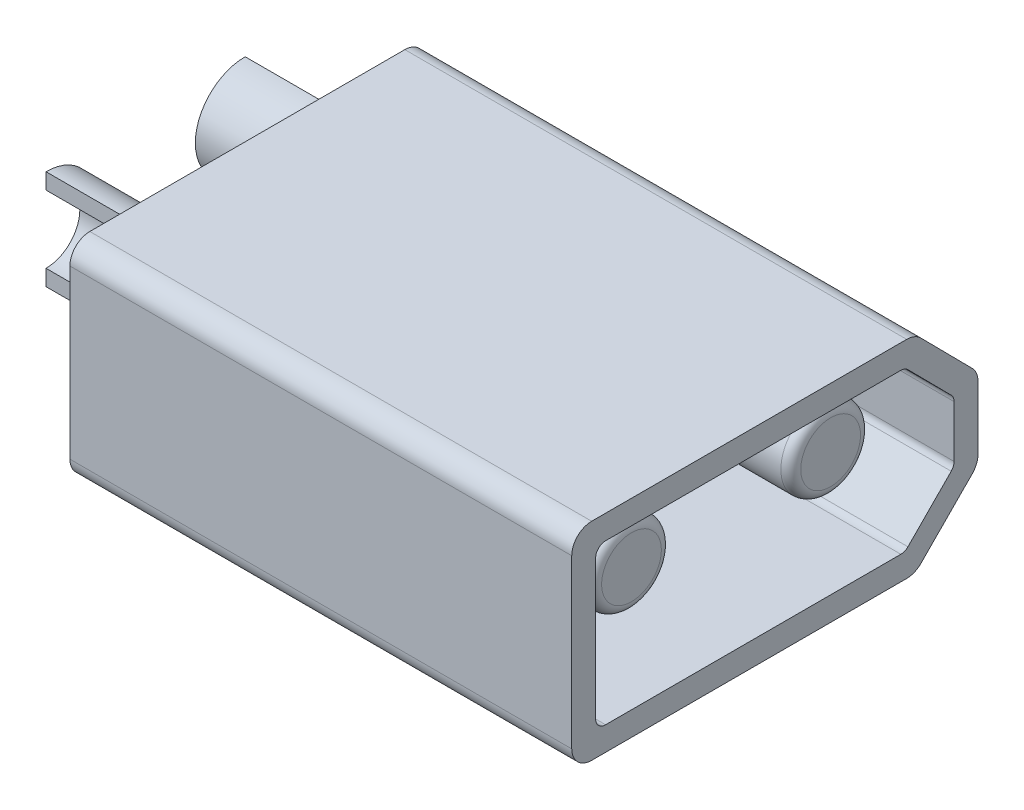
SolidWorks part; units mm, degrees
ref_plane "Front Plane" through (0, 0, 0) normal (0, 0, 1) x (1, 0, 0)
ref_plane "Top Plane" through (0, 0, 0) normal (0, 1, 0) x (1, 0, 0)
ref_plane "Right Plane" through (0, 0, 0) normal (1, 0, 0) x (0, 0, -1)
sketch "Sketch1" plane through (0, 0, 0) normal (1, 0, 0) x (0, 0, -1)
  line L0 (0, 0) -> (8.6181, 0)
  line L1 (8.6181, 0) -> (10.2, 1.6)
  line L2 (10.2, 1.6) -> (10.2, 3.6)
  line L3 (10.2, 3.6) -> (8.6181, 5.2)
  line L4 (8.6181, 5.2) -> (0, 5.2)
  line L5 (0, 5.2) -> (0, 0)
  line L6 (8.6181, 5.2) -> (8.6181, 0) construction
  dimension "D1" = 5.2
  dimension "D2" = 10.2
  dimension "D3" = 2.25
  dimension "D4" = 2
extrude "Boss-Extrude1" add sketch "Sketch1" along normal blind 12.6
sketch "Sketch2" plane through (12.6, 0, 0) normal (1, 0, 0) x (0, 0, -1)
  line L27 (9.6, 3.3535) -> (8.3675, 4.6)
  line L28 (8.3675, 0.6) -> (9.6, 1.8465)
  line L29 (9.6, 1.8465) -> (9.6, 3.3535)
  line L30 (0.6, 0.6) -> (8.3675, 0.6)
  line L31 (0.6, 4.6) -> (0.6, 0.6)
  line L32 (8.3675, 4.6) -> (0.6, 4.6)
  line L33 (9.6, 3.3535) -> (8.3675, 4.6)
  line L34 (8.3675, 0.6) -> (9.6, 1.8465)
  line L35 (9.6, 1.8465) -> (9.6, 3.3535)
  line L36 (0.6, 0.6) -> (8.3675, 0.6)
  line L37 (0.6, 4.6) -> (0.6, 0.6)
  line L38 (8.3675, 4.6) -> (0.6, 4.6)
  dimension "D1" = 0.6
extrude "Cut-Extrude1" cut sketch "Sketch2" against normal blind 7
sketch "Sketch3" plane through (0, 0, 0) normal (1, 0, 0) x (0, 0, -1)
  line L33 (9.6, 3.3535) -> (8.3675, 4.6)
  line L34 (8.3675, 0.6) -> (9.6, 1.8465)
  line L35 (9.6, 1.8465) -> (9.6, 3.3535)
  line L36 (0.6, 0.6) -> (8.3675, 0.6)
  line L37 (0.6, 4.6) -> (0.6, 0.6)
  line L38 (8.3675, 4.6) -> (0.6, 4.6)
extrude "Cut-Extrude2" cut sketch "Sketch3" along normal blind 3
sketch "Sketch5" plane through (5.6, 0, 0) normal (1, 0, 0) x (0, 0, -1)
  line L0 (0.6, 2.6) -> (9.6, 2.6) construction
  line L1 (0.6, 4.6) -> (0.6, 0.6) construction
  line L2 (9.6, 1.8465) -> (9.6, 3.3535) construction
  line L3 (7.6, 2.6) -> (2.6, 2.6) construction
  circle A0 centre (2.6, 2.6) radius 1
  circle A1 centre (7.6, 2.6) radius 1
  point P8 (0.6, 2.6)
  point P11 (9.6, 2.6)
  point P16 (5.1, 2.6)
  dimension "D1" = 2
  dimension "D2" = 5
extrude "Boss-Extrude2" add sketch "Sketch5" along normal blind 5.9
sketch "Sketch6" plane through (3, 0, 0) normal (-1, 0, 0) x (0, 0, 1)
  circle A0 centre (-7.6, 2.6) radius 1.25
  circle A1 centre (-2.6, 2.6) radius 1.25
  circle A2 centre (-7.6, 2.6) radius 1 construction
  circle A3 centre (-2.6, 2.6) radius 1 construction
  dimension "D1" = 2.5
extrude "Boss-Extrude3" add sketch "Sketch6" along normal blind 6.2
sketch "Sketch7" plane through (-3.2, 0, 0) normal (-1, 0, 0) x (0, 0, 1)
  circle A0 centre (-7.6, 2.6) radius 0.85
  circle A1 centre (-2.6, 2.6) radius 0.85
  circle A2 centre (-2.6, 2.6) radius 1.25 construction
  circle A3 centre (-7.6, 2.6) radius 1.25 construction
  dimension "D1" = 0.4
extrude "Cut-Extrude3" cut sketch "Sketch7" against normal blind 4.5
sketch "Sketch8" plane through (0, 5.2, 0) normal (0, 1, 0) x (1, 0, 0)
  line L0 (-0.9, 7.6) -> (-0.9, 2.6) construction
  line L1 (-4.2, 9.85) -> (-0.9, 9.85)
  line L2 (-4.2, 9.85) -> (-4.2, 7.6)
  line L3 (-4.2, 7.6) -> (-0.9, 7.6)
  line L4 (-0.9, 9.85) -> (-0.9, 7.6)
  line L5 (-4.2, 0.35) -> (-0.9, 0.35)
  line L6 (-4.2, 0.35) -> (-4.2, 2.6)
  line L7 (-4.2, 2.6) -> (-0.9, 2.6)
  line L8 (-0.9, 0.35) -> (-0.9, 2.6)
  line L9 (-3.2, 8.85) -> (-3.2, 6.35) construction
  line L10 (-3.2, 7.6) -> (3, 7.6) construction
  line L11 (-3.2, 2.6) -> (3, 2.6) construction
  line L12 (3, 8.85) -> (-3.2, 8.85) construction
  dimension "D1" = 2.3
  dimension "D2" = 1
  dimension "D3" = 1
extrude "Cut-Extrude4" cut sketch "Sketch8" against normal through all
sketch "Sketch9" plane through (3, 0, 0) normal (-1, 0, 0) x (0, 0, 1)
  line L0 (-6.811, 4.6) -> (-3.389, 4.6)
  line L1 (-3.389, 0.6) -> (-6.811, 0.6)
  line L2 (-8.3675, 4.6) -> (-0.6, 4.6) construction
  line L3 (-0.6, 0.6) -> (-8.3675, 0.6) construction
  line L4 (-3.389, 0.6) -> (-3.389, 4.6) construction
  line L5 (-6.811, 4.6) -> (-6.811, 0.6) construction
  arc A0 (-6.811, 4.6) -> (-6.811, 0.6) centre (-7.6, 2.6) cw
  arc A1 (-3.389, 4.6) -> (-3.389, 0.6) centre (-2.6, 2.6) ccw
  circle A2 centre (-7.6, 2.6) radius 1.25 construction
  circle A3 centre (-2.6, 2.6) radius 1.25 construction
  dimension "D1" = 2.15
extrude "Cut-Extrude5" cut sketch "Sketch9" against normal through all
fillet "Fillet1" radius 0.5 6 edges at (6.3, 5.2, 0) (6.3, 0, 0) (6.3, 0, -8.6181) (6.3, 1.6, -10.2) (6.3, 3.6, -10.2) (6.3, 5.2, -8.6181)
fillet "Fillet2" radius 0.25 12 edges at (9.1, 3.3535, -9.6) (9.1, 0.6, -8.3675) (9.1, 1.8465, -9.6) (9.1, 0.6, -0.6) (9.1, 4.6, -0.6) (9.1, 4.6, -8.3675) (1.5, 0.6, -8.3675) (1.5, 0.6, -0.6) (1.5, 1.8465, -9.6) (1.5, 3.3535, -9.6) (1.5, 4.6, -8.3675) (1.5, 4.6, -0.6)
fillet "Fillet3" radius 0.15 4 edges at (4.3, 0.6, -3.389) (4.3, 0.6, -6.811) (4.3, 4.6, -6.811) (4.3, 4.6, -3.389)
fillet "Fillet4" radius 0.25 2 edges at (11.5, 2.6, -3.6) (11.5, 2.6, -8.6)
ref_plane "Plane1" through (0, 2.6, 0) normal (0, -1, 0) x (-1, 0, 0)
sketch "Sketch10" plane through (12.6, 0, 0) normal (1, 0, 0) x (0, 0, -1)
  line L0 (0.5, 0) -> (8.4093, 0) construction
  line L1 (0, 5.2) -> (10.2, 5.2) construction
  line L2 (0, 5.2) -> (0, 0) construction
  line L3 (0, 0) -> (10.2, 0) construction
  line L4 (10.2, 5.2) -> (10.2, 0) construction
  line L5 (0, 4.7) -> (0, 0.5) construction
  line L6 (8.4093, 5.2) -> (0.5, 5.2) construction
  line L7 (10.2, 1.8054) -> (10.2, 3.3946) construction
  point P4 (5.1, 5.2)
  point P13 (5.1, 5.2)
  point P14 (5.1, 0)
  point P15 (5.1, 0)
ref_plane "Plane2" through (0, 0, -5.1) normal (0, 0, 1) x (1, 0, 0)
